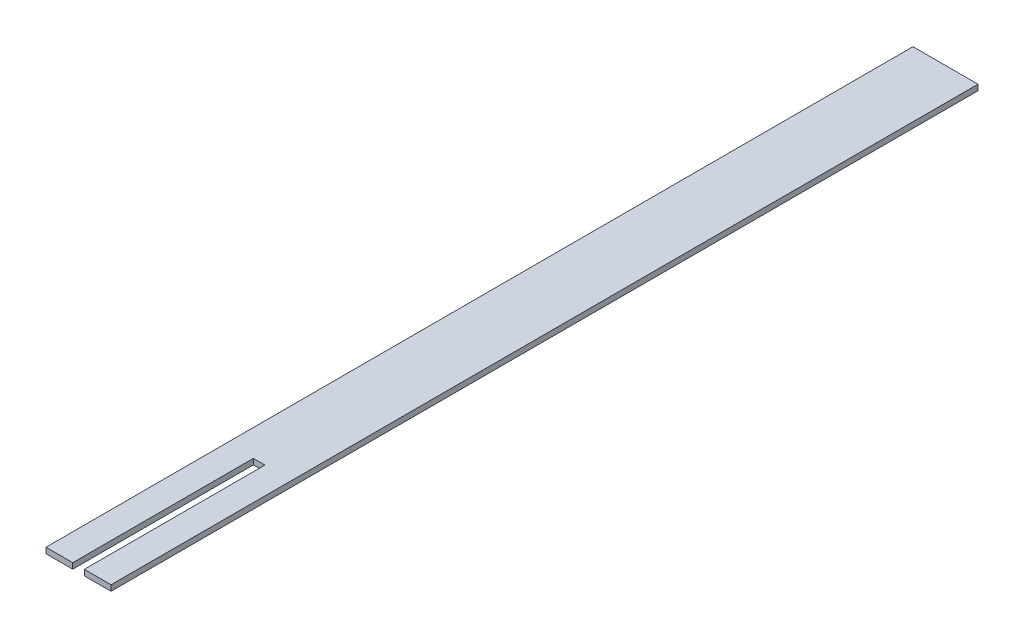
SolidWorks part; units mm, degrees
ref_plane "Front Plane" through (0, 0, 0) normal (0, 0, 1) x (1, 0, 0)
ref_plane "Top Plane" through (0, 0, 0) normal (0, 1, 0) x (1, 0, 0)
ref_plane "Right Plane" through (0, 0, 0) normal (1, 0, 0) x (0, 0, -1)
sketch "Sketch1" plane through (0, 0, 0) normal (0, 1, 0) x (1, 0, 0)
  line L0 (0, 0) -> (57.15, 0)
  line L1 (57.15, 0) -> (57.15, -762)
  line L2 (57.15, -762) -> (33.655, -762)
  line L3 (0, -762) -> (0, 0)
  line L4 (23.495, -762) -> (23.495, -603.25)
  line L5 (23.495, -603.25) -> (33.655, -603.25)
  line L6 (33.655, -603.25) -> (33.655, -762)
  line L7 (23.495, -762) -> (0, -762)
  dimension "D1" = 762
  dimension "D2" = 57.15
  dimension "D3" = 10.16
  dimension "D4" = 158.75
extrude "Boss-Extrude1" add sketch "Sketch1" along normal blind 5 contours L3 L0 L1 L2 L6 L5 L4 L7
